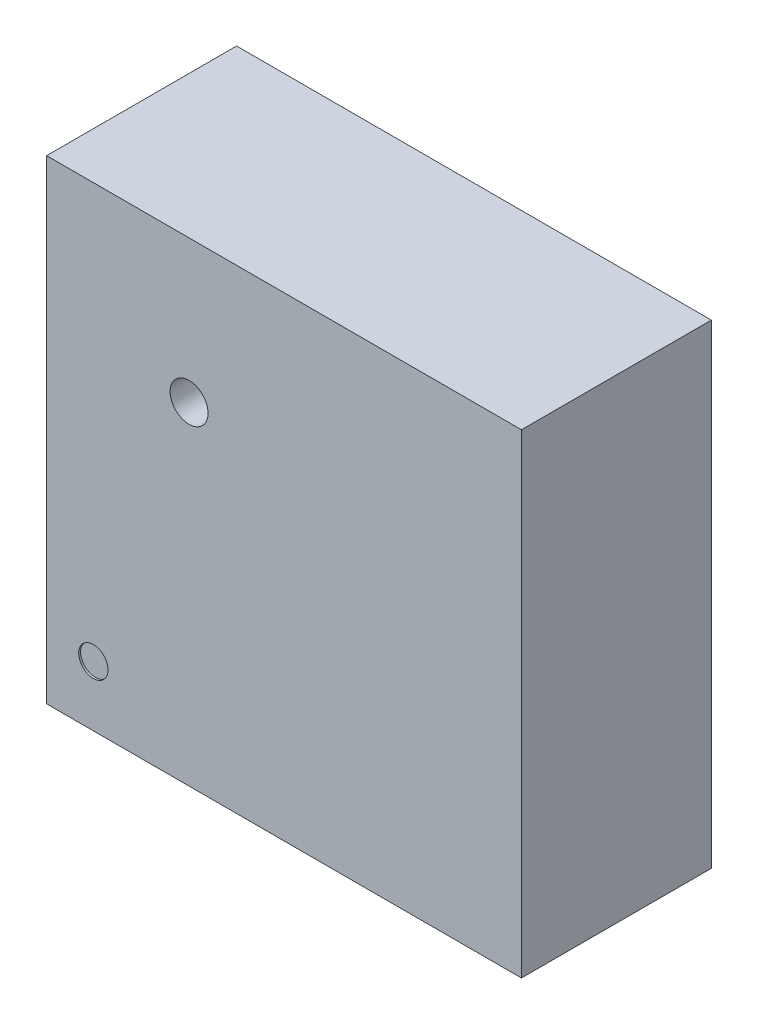
SolidWorks part; units mm, degrees
ref_plane "Front Plane" through (0, 0, 0) normal (0, 0, 1) x (1, 0, 0)
ref_plane "Top Plane" through (0, 0, 0) normal (0, 1, 0) x (1, 0, 0)
ref_plane "Right Plane" through (0, 0, 0) normal (1, 0, 0) x (0, 0, -1)
sketch "Sketch1" plane through (0, 0, 0) normal (0, 0, 1) x (1, 0, 0)
  line L1 (-1.25, -1.25) -> (1.25, -1.25)
  line L2 (-1.25, -1.25) -> (-1.25, 1.25)
  line L3 (-1.25, 1.25) -> (1.25, 1.25)
  line L4 (1.25, -1.25) -> (1.25, 1.25)
  line L5 (-1.25, -1.25) -> (1.25, 1.25) construction
  line L6 (-1.25, 1.25) -> (1.25, -1.25) construction
  point P0 (0, 0)
  dimension "D1" = 2.5
  dimension "D2" = 2.5
extrude "Boss-Extrude1" add sketch "Sketch1" along normal blind 1
sketch "Sketch2" plane through (0, 0, 1) normal (0, 0, 1) x (1, 0, 0)
  line L0 (-1.25, 0) -> (1.25, 0) construction
  line L1 (-1.25, 1.25) -> (-1.25, -1.25) construction
  line L2 (1.25, -1.25) -> (1.25, 1.25) construction
  line L3 (0, -1.25) -> (0, 1.25) construction
  line L4 (-1.25, -1.25) -> (1.25, -1.25) construction
  line L5 (1.25, 1.25) -> (-1.25, 1.25) construction
  circle A0 centre (-0.5, 0.5) radius 0.1
  dimension "D1" = 0.2
  dimension "D2" = 0.5
  dimension "D3" = 0.5
extrude "Cut-Extrude1" cut sketch "Sketch2" against normal blind 0.2 contours A0
sketch "Sketch3" plane through (0, 0, 1) normal (0, 0, 1) x (1, 0, 0)
  circle A0 centre (-1.004, -0.9338) radius 0.0773
extrude "Cut-Extrude2" cut sketch "Sketch3" against normal blind 0.01
